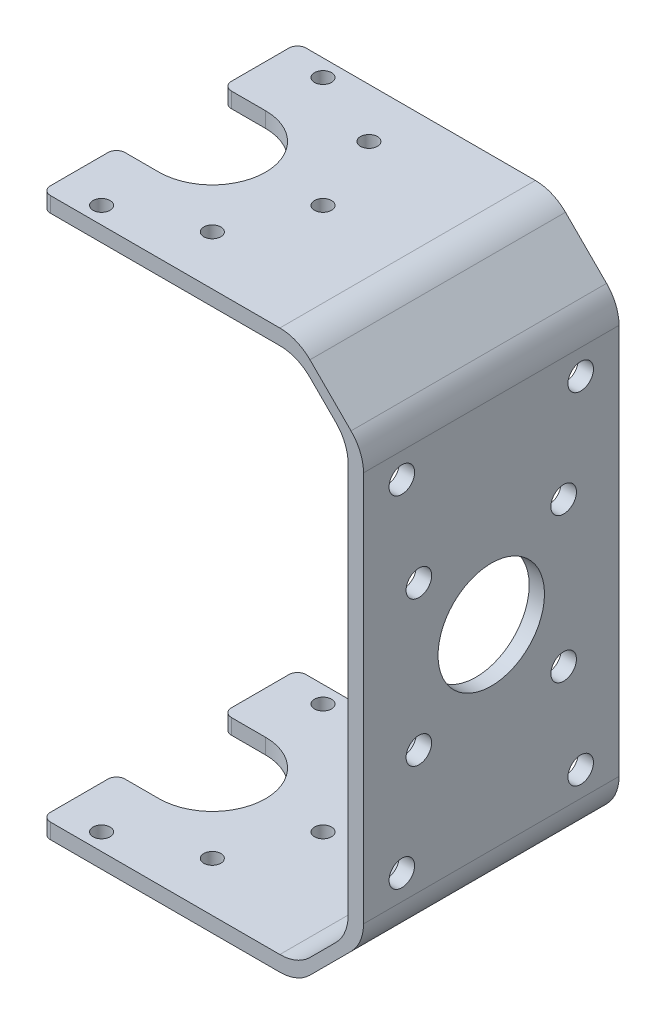
SolidWorks part; units mm, degrees
ref_plane "正面" through (0, 0, 0) normal (0, 0, 1) x (1, 0, 0)
ref_plane "平面" through (0, 0, 0) normal (0, 1, 0) x (1, 0, 0)
ref_plane "右側面" through (0, 0, 0) normal (1, 0, 0) x (0, 0, -1)
sketch "ｽｹｯﾁ1" plane through (0, 0, 0) normal (1, 0, 0) x (0, 0, -1)
  line L1 (-15, 25) -> (15, 25)
  line L2 (-15, 25) -> (-15, -25)
  line L3 (-15, -25) -> (15, -25)
  line L4 (15, 25) -> (15, -25)
  line L5 (-15, 25) -> (15, -25) construction
  line L6 (-15, -25) -> (15, 25) construction
  point P0 (0, 0)
  dimension "D1" = 50
  dimension "D2" = 30
extrude "ﾎﾞｽ - 押し出し1" add sketch "ｽｹｯﾁ1" along normal mid plane 1.8
sketch "ｽｹｯﾁ2" plane through (0.9, 0, 0) normal (1, 0, 0) x (0, 0, -1)
  line L0 (-15, 25) -> (-15, -25) construction
  line L1 (15, 25) -> (-15, 25) construction
  line L2 (0, 0.99) -> (0, -0.99) construction
  line L3 (0.99, 0) -> (-0.99, 0) construction
  circle A0 centre (0, 0) radius 6.25
  circle A1 centre (-10.5, 20) radius 1.5
  circle A2 centre (10.5, 20) radius 1.5
  circle A3 centre (10.5, -20) radius 1.5
  circle A4 centre (-10.5, -20) radius 1.5
  circle A5 centre (-8.5, 8.5) radius 1.5
  circle A6 centre (8.5, 8.5) radius 1.5
  circle A7 centre (8.5, -8.5) radius 1.5
  circle A8 centre (-8.5, -8.5) radius 1.5
  dimension "D1" = 12.5
  dimension "D2" = 3
  dimension "D5" = 3
  dimension "D3" = 4.5
  dimension "D4" = 5
  dimension "D6" = 6.5
  dimension "D7" = 16.5
extrude "ｶｯﾄ - 押し出し1" cut sketch "ｽｹｯﾁ2" against normal blind 1.8
sketch "ｽｹｯﾁ3" plane through (0, 0, -15) normal (0, 0, -1) x (-1, 0, 0)
  line L0 (-0.9, 25) -> (6.85, 32.75)
  line L1 (6.85, 32.75) -> (36.85, 32.75)
  line L2 (36.85, 32.75) -> (36.85, 30.95)
  line L3 (36.85, 30.95) -> (7.85, 30.95)
  line L5 (0.9, 25) -> (-0.9, 25)
  line L6 (0.9, 25) -> (6.85, 30.95)
  line L7 (6.85, 30.95) -> (7.85, 30.95)
  dimension "D1" = 7.75
  dimension "D2" = 45
  dimension "D3" = 30
  dimension "D4" = 1.8
  dimension "D5" = 1
  dimension "D6" = 29
extrude "ﾎﾞｽ - 押し出し2" add sketch "ｽｹｯﾁ3" against normal blind 30
sketch "ｽｹｯﾁ4" plane through (0, 32.75, 0) normal (0, 1, 0) x (1, 0, 0)
  line L0 (-36.85, -15) -> (-36.85, 15) construction
  line L6 (-31.85, -6.25) -> (-36.85, -6.25)
  line L7 (-36.85, -6.25) -> (-36.85, 6.25)
  line L10 (-36.85, 6.25) -> (-31.85, 6.25)
  line L11 (-31.85, 6.25) -> (-31.85, -6.25)
  circle A0 centre (-31.85, 0) radius 6.25
  circle A1 centre (-31.85, 13) radius 1
  circle A6 centre (-22.6576, 9.1924) radius 1
  circle A7 centre (-18.85, 0) radius 1
  circle A8 centre (-22.6576, -9.1924) radius 1
  circle A9 centre (-31.85, -13) radius 1
  point P4 (-38.1, 0)
  dimension "D1" = 12.5
  dimension "D3" = 2
  dimension "D2" = 5
  dimension "D4" = 13
  dimension "D6" = 0
  dimension "D5" = 5
extrude "ｶｯﾄ - 押し出し2" cut sketch "ｽｹｯﾁ4" against normal blind 1.8
mirror "ﾐﾗｰ2" about plane through (0, 0, 0) normal (0, 1, 0) of "ﾎﾞｽ - 押し出し2"
fillet "ﾌｨﾚｯﾄ1" radius 5 8 edges at (-6.85, -30.95, 0) (-0.9, -25, 0) (-0.9, 25, 0) (-6.85, 30.95, 0) (-6.85, -32.75, 0) (0.9, -25, 0) (0.9, 25, 0) (-6.85, 32.75, 0)
sketch "ｽｹｯﾁ5" plane through (0, -32.75, 0) normal (0, -1, 0) x (1, 0, 0)
  line L0 (-36.85, 15) -> (-36.85, -15) construction
  line L4 (-31.85, -6.25) -> (-31.85, 6.25)
  line L7 (-31.85, 6.25) -> (-36.85, 6.25)
  line L8 (-36.85, 6.25) -> (-36.85, -6.25)
  line L9 (-36.85, -6.25) -> (-31.85, -6.25)
  circle A0 centre (-31.85, 0) radius 6.25
  circle A1 centre (-31.85, 13) radius 1
  circle A6 centre (-22.6576, 9.1924) radius 1
  circle A7 centre (-18.85, 0) radius 1
  circle A8 centre (-22.6576, -9.1924) radius 1
  circle A9 centre (-31.85, -13) radius 1
  dimension "D1" = 12.5
  dimension "D3" = 2
  dimension "D2" = 5
  dimension "D4" = 13
  dimension "D5" = 5
extrude "ｶｯﾄ - 押し出し3" cut sketch "ｽｹｯﾁ5" against normal blind 1.8
fillet "ﾌｨﾚｯﾄ2" radius 1 8 edges at (-36.85, -31.85, -6.25) (-36.85, -31.85, -15) (-36.85, -31.85, 6.25) (-36.85, -31.85, 15) (-36.85, 31.85, -6.25) (-36.85, 31.85, -15) (-36.85, 31.85, 6.25) (-36.85, 31.85, 15)
